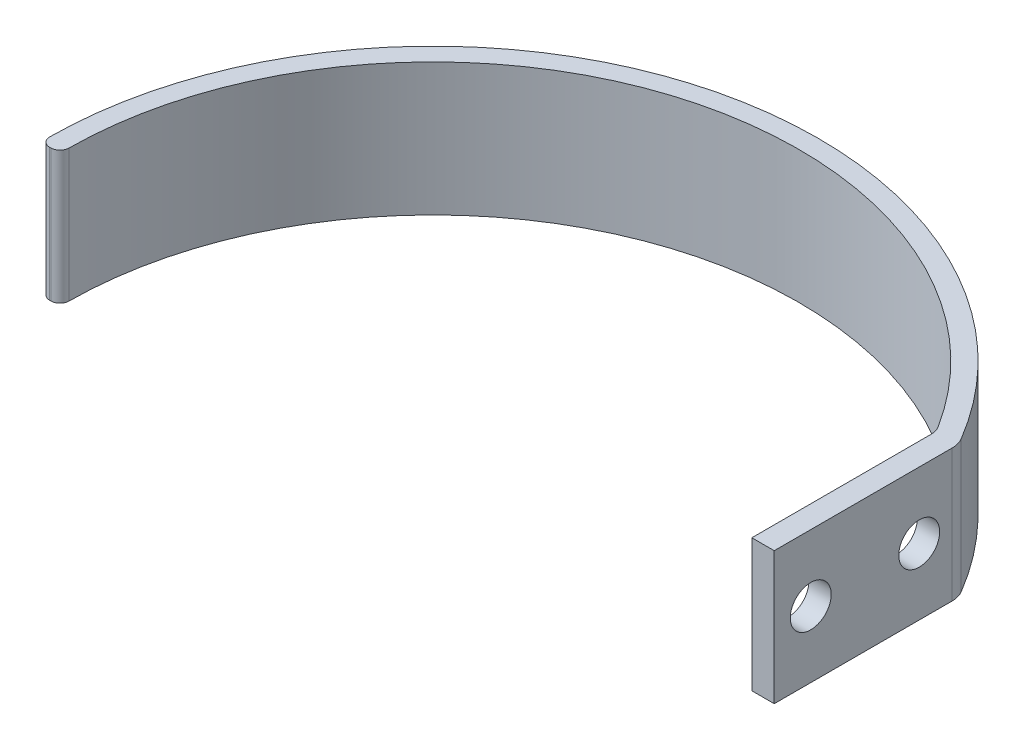
SolidWorks part; units mm, degrees
ref_plane "Front Plane" through (0, 0, 0) normal (0, 0, 1) x (1, 0, 0)
ref_plane "Top Plane" through (0, 0, 0) normal (0, 1, 0) x (1, 0, 0)
ref_plane "Right Plane" through (0, 0, 0) normal (1, 0, 0) x (0, 0, -1)
sketch "Sketch1" plane through (0, 0, 0) normal (0, 1, 0) x (1, 0, 0)
  line L0 (-31.9955, -0.5364) -> (-30.3955, -0.5364)
  line L1 (31.9955, 0.5364) -> (30.3955, 0.5364)
  arc A0 (31.9955, 0.5364) -> (-31.9955, -0.5364) centre (0, 0) ccw
  arc A1 (-30.3955, -0.5364) -> (30.3955, 0.5364) centre (0, 0) cw
  dimension "D1" = 32
  dimension "D2" = 1.6
extrude "Boss-Extrude1" add sketch "Sketch1" along normal blind 11 contours A1 L1 A0 L0
sketch "Sketch2" plane through (0, 11, 0) normal (0, 1, 0) x (1, 0, 0)
  line L1 (31.9955, 0.5364) -> (25.9435, 0.5364)
  line L2 (31.9955, 0.5364) -> (31.9955, 15.8464)
  line L3 (31.9955, 15.8464) -> (25.9435, 15.8464)
  line L4 (25.9435, 0.5364) -> (25.9435, 15.8464)
  arc A0 (30.3955, 0.5364) -> (-30.3955, -0.5364) centre (0, 0) ccw construction
  dimension "D1" = 15.31
  dimension "D2" = 6.052
extrude "Boss-Extrude2" add sketch "Sketch2" against normal through all
fillet "Fillet2" radius 1.5 1 edges at (25.9435, 5.5, -15.8464)
fillet "Fillet4" radius 0.75 2 edges at (-31.9955, 5.5, 0.5364) (-30.3955, 5.5, 0.5364)
sketch "Sketch5" plane through (0, 11, 0) normal (0, 1, 0) x (1, 0, 0)
  line L0 (31.9955, 0.5364) -> (25.9435, 0.5364) construction
  line L1 (31.9955, 15.8464) -> (27.8009, 15.8464)
  line L2 (31.9955, 15.8464) -> (31.9955, 0.5364)
  line L3 (31.9955, 0.5364) -> (27.8009, 0.5364)
  line L4 (27.8009, 15.8464) -> (27.8009, 0.5364)
extrude "Cut-Extrude4" cut sketch "Sketch5" against normal up to next
fillet "Fillet6" radius 2 1 edges at (27.8009, 5.5, -15.8464)
hole_wizard "M3 Clearance Hole1" positions "Sketch6" profile "Sketch7" hole size "M3" standard "ANSI Metric"
sketch "Sketch6" plane through (27.8009, 0, 0) normal (1, 0, 0) x (0, 0, -1)
  line L0 (15.3072, 0) -> (0.5364, 0) construction
  line L1 (0.5364, 0) -> (0.5364, 11) construction
  point P0 (12.5664, 5.5)
  point P2 (3.5664, 5.5)
  dimension "D1" = 9
  dimension "D2" = 5.5
  dimension "D3" = 3.03
sketch "Sketch7" plane through (27.8009, 5.5, -12.5664) normal (0, 1, 0) x (0, 0, -1)
  line L0 (0, 0) -> (0, 2.8779)
  line L1 (0, 2.8779) -> (1.7, 1.8564)
  line L2 (1.7, 1.8564) -> (1.7, 0)
  line L5 (1.7, 0) -> (0, 0)
  line L10 (0, 2.8779) -> (-1.7, 1.8564) construction
  line L11 (0, -6.35) -> (0, 107.95) construction
  dimension "Hole Dia." = 3.4
  dimension "Hole Depth" = 1.8564
  dimension "Drill Angle" = 118
